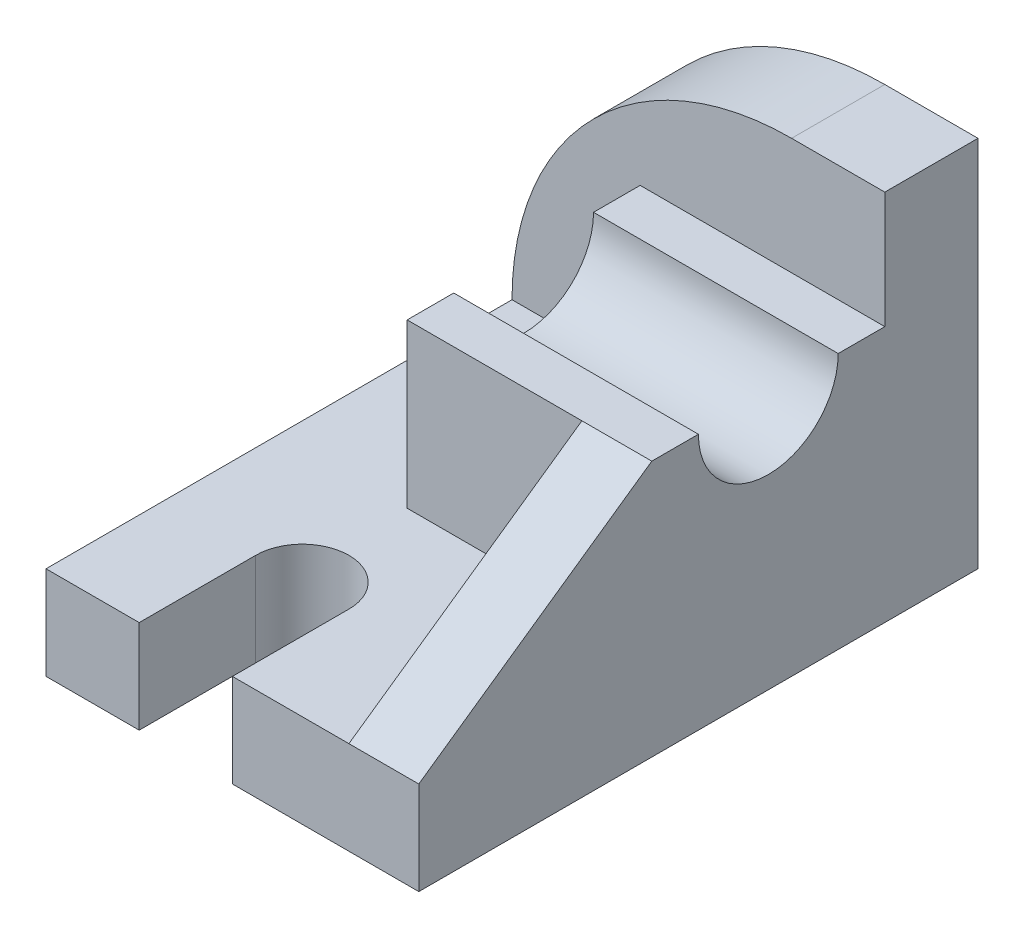
SolidWorks part; units mm, degrees
ref_plane "Front Plane" through (0, 0, 0) normal (0, 0, 1) x (1, 0, 0)
ref_plane "Top Plane" through (0, 0, 0) normal (0, 1, 0) x (1, 0, 0)
ref_plane "Right Plane" through (0, 0, 0) normal (1, 0, 0) x (0, 0, -1)
sketch "Sketch1" plane through (0, 0, 0) normal (0, 1, 0) x (1, 0, 0)
  line L1 (0, 0) -> (64, 0)
  line L2 (0, 0) -> (0, 96)
  line L3 (0, 96) -> (64, 96)
  line L4 (64, 0) -> (64, 96)
  dimension "D1" = 96
  dimension "D2" = 64
extrude "Boss-Extrude1" add sketch "Sketch1" along normal blind 16
sketch "Sketch12" plane through (0, 0, 0) normal (0, 1, 0) x (1, 0, 0)
  line L0 (24, 0) -> (24, 20) construction
  line L1 (0, 0) -> (64, 0) construction
  line L2 (16, 0) -> (16, 20)
  line L3 (32, 0) -> (32, 20)
  line L4 (0, 96) -> (0, 0) construction
  arc A0 (16, 0) -> (32, 0) centre (24, 0) ccw
  arc A1 (32, 20) -> (16, 20) centre (24, 20) ccw
  point P4 (24, 10)
  dimension "D1" = 16
  dimension "D2" = 20
  dimension "D3" = 16
extrude "Cut-Extrude1" cut sketch "Sketch12" along normal blind 16
sketch "Sketch14" plane through (0, 0, -96) normal (0, 0, -1) x (-1, 0, 0)
  line L1 (0, 0) -> (-64, 0)
  line L2 (0, 0) -> (0, 16)
  line L3 (-48, 64) -> (-64, 64)
  line L4 (-64, 0) -> (-64, 64)
  arc A0 (0, 16) -> (-48, 64) centre (-48, 16) ccw
  point P7 (0, 64)
  dimension "D3" = 48
  dimension "D1" = 64
  dimension "D2" = 64
extrude "Boss-Extrude2" add sketch "Sketch14" against normal blind 16
sketch "Sketch15" plane through (64, 0, 0) normal (1, 0, 0) x (0, 0, -1)
  line L1 (80, 16) -> (40, 16)
  line L2 (80, 16) -> (80, 44)
  line L3 (80, 44) -> (40, 44)
  line L4 (40, 16) -> (40, 44)
  dimension "D1" = 40
  dimension "D2" = 28
extrude "Boss-Extrude3" add sketch "Sketch15" against normal blind 42
sketch "Sketch16" plane through (22, 0, 0) normal (-1, 0, 0) x (0, 0, 1)
  line L0 (-80, 44) -> (-40, 44) construction
  circle A0 centre (-60, 44) radius 12
  dimension "D1" = 24
extrude "Cut-Extrude2" cut sketch "Sketch16" against normal through all
sketch "Sketch17" plane through (64, 0, 0) normal (1, 0, 0) x (0, 0, -1)
  line L0 (0, 16) -> (40, 16)
  line L1 (40, 16) -> (40, 44)
  line L2 (40, 44) -> (0, 16)
extrude "Boss-Extrude4" add sketch "Sketch17" against normal blind 12
